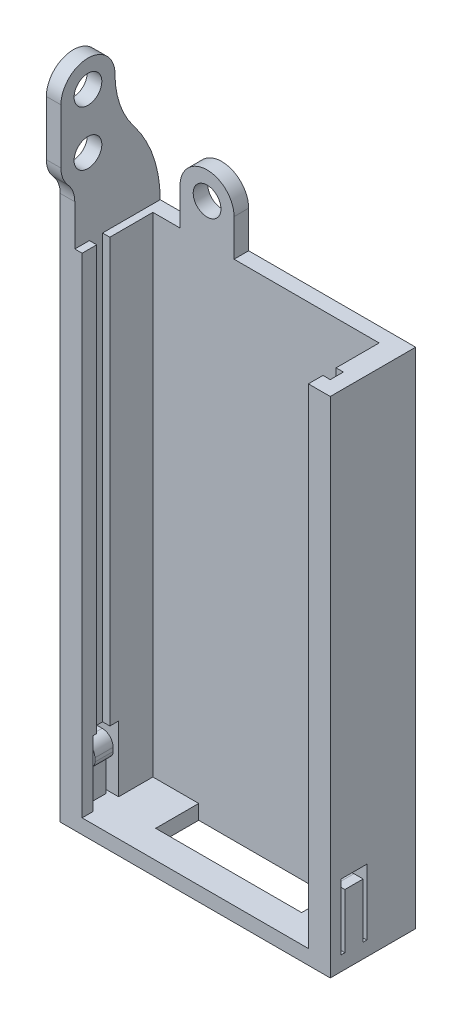
SolidWorks part; units mm, degrees
ref_plane "Front Plane" through (0, 0, 0) normal (0, 0, 1) x (1, 0, 0)
ref_plane "Top Plane" through (0, 0, 0) normal (0, 1, 0) x (1, 0, 0)
ref_plane "Right Plane" through (0, 0, 0) normal (1, 0, 0) x (0, 0, -1)
sketch "Sketch1" plane through (0, 0, 0) normal (0, 1, 0) x (1, 0, 0)
  line L1 (0, 0) -> (37, 0)
  line L2 (0, 0) -> (0, 11.7)
  line L3 (0, 11.7) -> (37, 11.7)
  line L4 (37, 0) -> (37, 11.7)
  dimension "D1" = 37
  dimension "D2" = 11.7
extrude "Boss-Extrude1" add sketch "Sketch1" along normal blind 69
sketch "Sketch2" plane through (0, 69, 0) normal (0, 1, 0) x (1, 0, 0)
  line L0 (3, 0) -> (3, 2)
  line L1 (0, 0) -> (37, 0) construction
  line L2 (3, 2) -> (2, 2)
  line L4 (3, 9.7) -> (34, 9.7)
  line L7 (35, 2) -> (34, 2)
  line L8 (34, 2) -> (34, 0)
  line L9 (3, 0) -> (34, 0)
  line L10 (37, 11.7) -> (0, 11.7) construction
  line L13 (3, 9.7) -> (3, 3.8)
  line L14 (3, 3.8) -> (2, 3.8)
  line L15 (2, 3.8) -> (2, 2)
  line L16 (35, 2) -> (35, 3.8)
  line L17 (35, 3.8) -> (34, 3.8)
  line L18 (34, 3.8) -> (34, 9.7)
  point P11 (18.5, 0)
  point P12 (18.5, 0)
  dimension "D1" = 2
  dimension "D2" = 1.8
  dimension "D3" = 2
  dimension "D4" = 33
  dimension "D5" = 1
extrude "Cut-Extrude1" cut sketch "Sketch2" against normal blind 67
sketch "Sketch3" plane through (0, 2, 0) normal (0, 1, 0) x (1, 0, 0)
  line L0 (34, 9.7) -> (3, 9.7) construction
  line L1 (9.275, 9.7) -> (29.275, 9.7)
  line L2 (9.275, 9.7) -> (9.275, 3.8)
  line L3 (9.275, 3.8) -> (29.275, 3.8)
  line L4 (29.275, 9.7) -> (29.275, 3.8)
  line L5 (35, 3.8) -> (34, 3.8) construction
  line L6 (3, 9.7) -> (3, 3.8) construction
  dimension "D1" = 20
  dimension "D2" = 6.275
extrude "Cut-Extrude2" cut sketch "Sketch3" against normal blind 67
sketch "Sketch5" plane through (0, 0, -11.7) normal (0, 0, -1) x (-1, 0, 0)
  line L1 (-37, 69) -> (0, 69) construction
  line L2 (-14.12, 74.05) -> (-14.12, 69)
  line L3 (-6.72, 74.05) -> (-6.72, 69)
  line L4 (-14.12, 69) -> (-6.72, 69)
  circle A0 centre (-10.42, 74.05) radius 1.9
  arc A1 (-6.72, 74.05) -> (-14.12, 74.05) centre (-10.42, 74.05) ccw
  dimension "D3" = 3.8
  dimension "D4" = 1.8
  dimension "D1" = 10.42
  dimension "D2" = 5.05
extrude "Boss-Extrude3" add sketch "Sketch5" against normal blind 2
sketch "Sketch7" plane through (0, 0, 0) normal (-1, 0, 0) x (0, 0, 1)
  line L1 (1.9, 87.05) -> (1.9, 79.55)
  line L7 (-11.7, 69) -> (0, 69) construction
  line L8 (0, 69) -> (-11.7, 69)
  line L9 (-11.7, 69) -> (-11.7, 80.4669) construction
  line L13 (0, 74.5992) -> (0, 69)
  circle A0 centre (-1.8, 79.55) radius 1.9
  circle A1 centre (-1.8, 87.05) radius 1.9
  arc A4 (1.9, 87.05) -> (-5.5, 87.05) centre (-1.8, 87.05) ccw
  arc A5 (-5.5, 87.05) -> (-8.0762, 79.55) centre (-17.7054, 87.05) cw
  arc A6 (-8.0762, 79.55) -> (-11.7, 69) centre (5.469, 69) ccw
  arc A7 (1.9, 79.55) -> (0.95, 77.0746) centre (-1.8, 79.55) cw
  arc A9 (0.95, 77.0746) -> (0, 74.5992) centre (3.7, 74.5992) ccw
  dimension "D2" = 3.8
  dimension "D3" = 3.8
  dimension "D6" = 1.8
  dimension "D7" = 1.8
  dimension "D1" = 1.8
  dimension "D4" = 10.55
  dimension "D5" = 18.05
extrude "Boss-Extrude4" add sketch "Sketch7" against normal blind 2
sketch "Sketch8" plane through (37, 0, 0) normal (1, 0, 0) x (0, 0, -1)
  line L0 (0, 69) -> (0, 0) construction
  line L1 (1.5, 2) -> (5, 2)
  line L2 (1.5, 2) -> (1.5, 11)
  line L3 (1.5, 11) -> (5, 11)
  line L4 (5, 2) -> (5, 11)
  line L5 (0, 0) -> (11.7, 0) construction
  dimension "D1" = 1.5
  dimension "D2" = 3.5
  dimension "D3" = 2
  dimension "D4" = 9
extrude "Cut-Extrude3" cut sketch "Sketch8" against normal blind 40
sketch "Sketch9" plane through (0, 0, -5) normal (0, 0, 1) x (1, 0, 0)
  line L0 (37, 2) -> (37, 9.5)
  line L1 (37, 69) -> (37, 0) construction
  line L2 (37, 9.5) -> (35.75, 9.5)
  line L3 (34.25, 8) -> (34.25, 7.5)
  line L4 (35.25, 6.5) -> (35.25, 2)
  line L5 (35.25, 2) -> (37, 2)
  arc A0 (35.75, 9.5) -> (34.25, 8) centre (35.75, 8) ccw
  arc A1 (34.25, 7.5) -> (35.25, 6.5) centre (35.25, 7.5) ccw
  dimension "D4" = 1
  dimension "D1" = 7.5
  dimension "D2" = 4.5
  dimension "D3" = 1.25
  dimension "D5" = 1.75
extrude "Boss-Extrude5" add sketch "Sketch9" along normal blind 2.5 from offset 0.5
ref_plane "Plane1" through (18.5, 0, 0) normal (1, 0, 0) x (0, 0, -1)
mirror "Mirror1" about plane through (18.5, 0, 0) normal (1, 0, 0) of "Boss-Extrude5"
